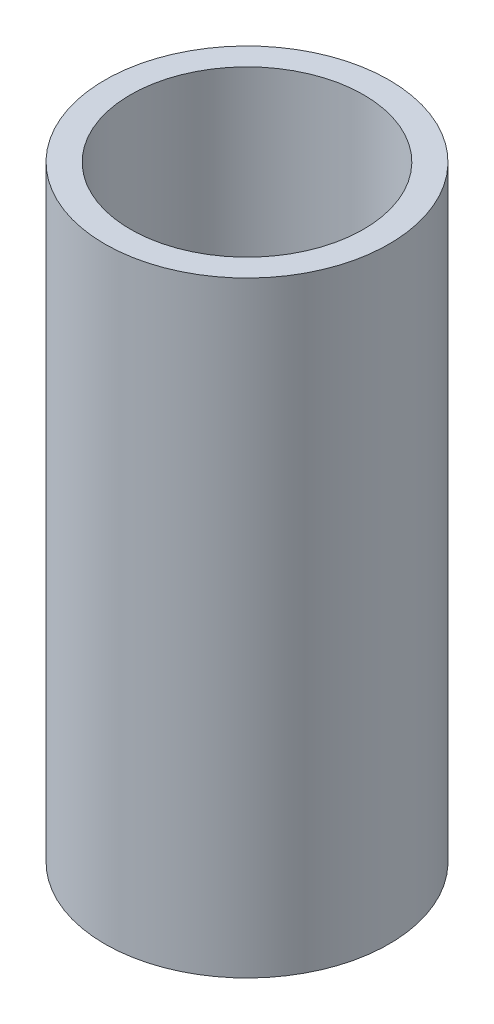
SolidWorks part; units mm, degrees
ref_plane "Front Plane" through (0, 0, 0) normal (0, 0, 1) x (1, 0, 0)
ref_plane "Top Plane" through (0, 0, 0) normal (0, 1, 0) x (1, 0, 0)
ref_plane "Right Plane" through (0, 0, 0) normal (1, 0, 0) x (0, 0, -1)
sketch "Sketch1" plane through (0, 0, 0) normal (0, 1, 0) x (1, 0, 0)
  circle A0 centre (0, 0) radius 3.048
  circle A1 centre (0, 0) radius 2.5
  dimension "D1" = 6.096
  dimension "D2" = 5
extrude "Boss-Extrude1" add sketch "Sketch1" along normal mid plane 13
